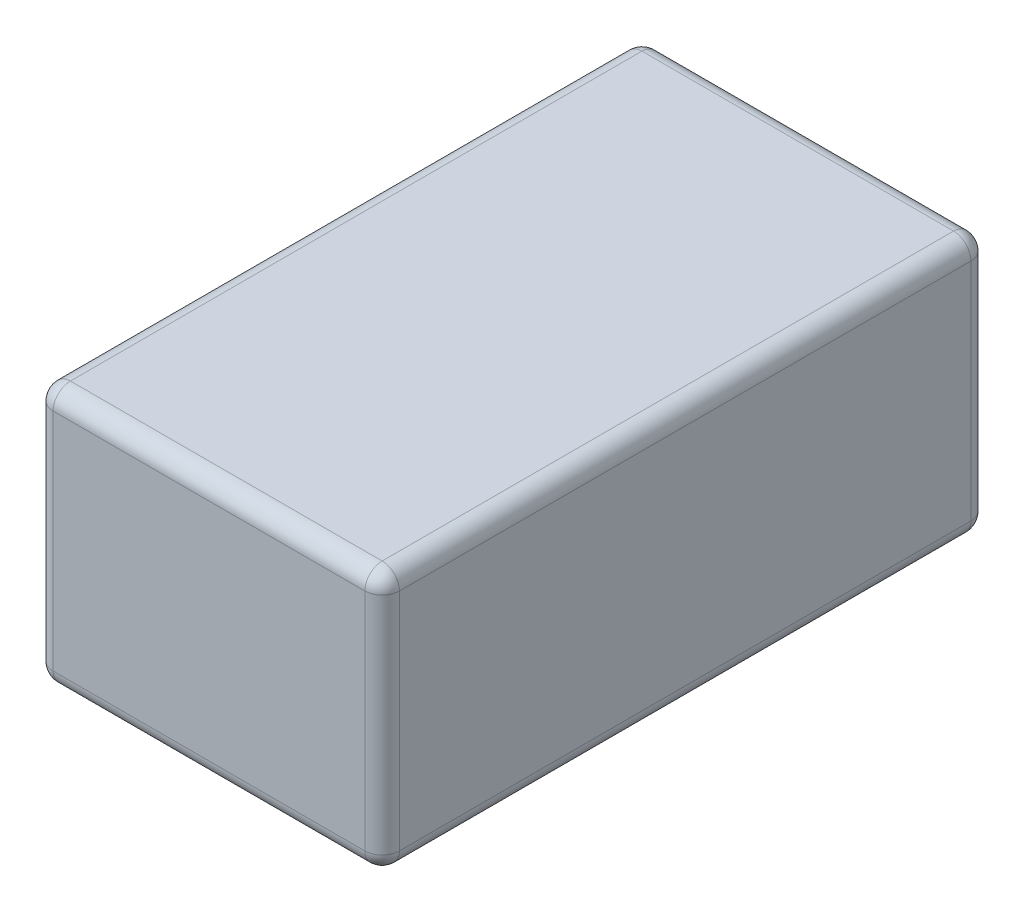
SolidWorks part; units mm, degrees
material "Thornel Mat VMA"
ref_plane "Přední rovina" through (0, 0, 0) normal (0, 0, 1) x (1, 0, 0)
ref_plane "Horní rovina" through (0, 0, 0) normal (0, 1, 0) x (1, 0, 0)
ref_plane "Pravá rovina" through (0, 0, 0) normal (1, 0, 0) x (0, 0, -1)
sketch "Skica1" plane through (0, 0, 0) normal (0, 1, 0) x (1, 0, 0)
  line L0 (-10, -17.5) -> (10, 17.5) construction
  line L1 (-10, 17.5) -> (10, 17.5)
  line L2 (-10, 17.5) -> (-10, -17.5)
  line L3 (-10, -17.5) -> (10, -17.5)
  line L4 (10, 17.5) -> (10, -17.5)
  line L5 (10, 17.5) -> (9.5603, 15.7414) construction
  dimension "D1" = 35
  dimension "D2" = 20
extrude "Přidat vysunutím1" add sketch "Skica1" along normal mid plane 15
fillet "Zaoblit1" radius 1 12 edges at (10, 0, -17.5) (-10, 0, -17.5) (-10, 0, 17.5) (10, 0, 17.5) (0, -7.5, 17.5) (10, -7.5, 0) (0, -7.5, -17.5) (-10, -7.5, 0) (0, 7.5, -17.5) (10, 7.5, 0) (0, 7.5, 17.5) (-10, 7.5, 0)
